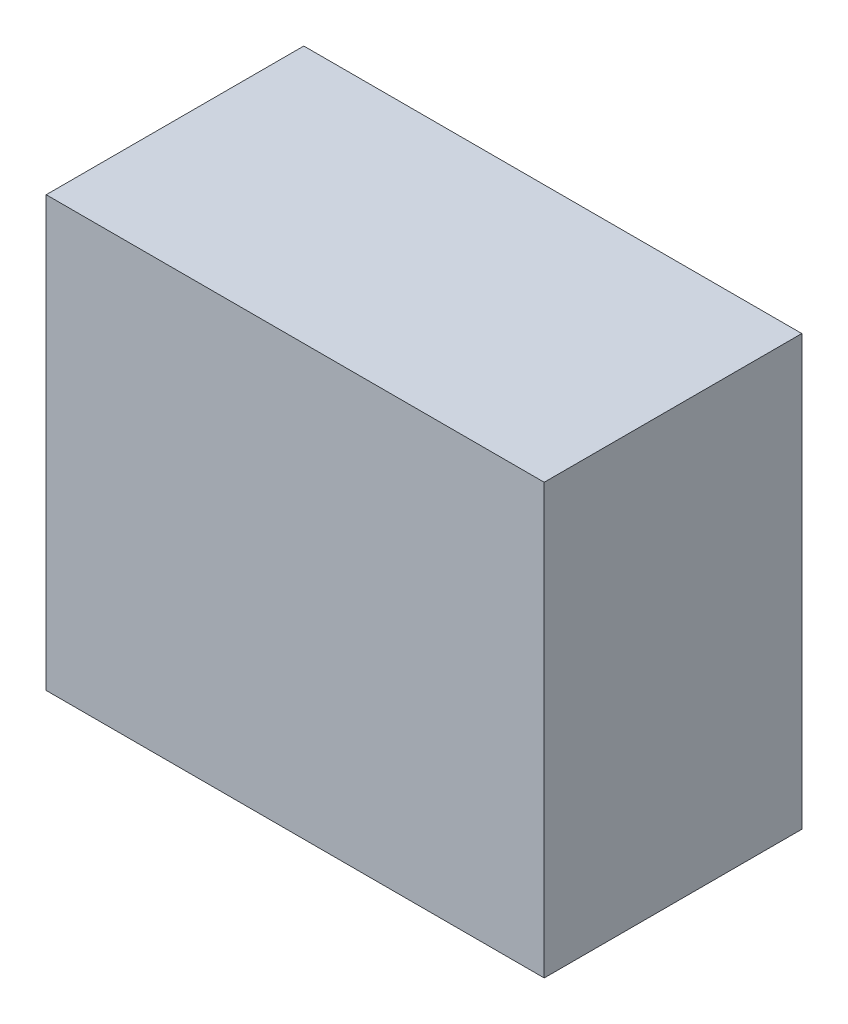
SolidWorks part; units mm, degrees
ref_plane "Front" through (0, 0, 0) normal (0, 0, 1) x (1, 0, 0)
ref_plane "Top" through (0, 0, 0) normal (0, 1, 0) x (1, 0, 0)
ref_plane "Right" through (0, 0, 0) normal (1, 0, 0) x (0, 0, -1)
sketch "Sketch1" plane through (0, 0, 0) normal (0, 0, 1) x (1, 0, 0)
  line L1 (0, 0) -> (29.464, 0)
  line L2 (0, 0) -> (0, 25.4)
  line L3 (0, 25.4) -> (29.464, 25.4)
  line L4 (29.464, 0) -> (29.464, 25.4)
  dimension "D1" = 29.464
  dimension "D2" = 25.4
extrude "Boss-Extrude1" add sketch "Sketch1" along normal blind 15.24
sketch "Sketch2" plane through (0, 0, 0) normal (0, -1, 0) x (1, 0, 0)
  line L0 (0, 0) -> (29.464, 0) construction
  line L1 (4.6228, 13.335) -> (24.765, 13.335)
  line L2 (4.6228, 13.335) -> (4.6228, 1.905)
  line L3 (4.6228, 1.905) -> (24.765, 1.905)
  line L4 (24.765, 13.335) -> (24.765, 1.905)
  line L6 (29.464, 15.24) -> (29.464, 0) construction
  dimension "D1" = 20.1422
  dimension "D2" = 11.43
  dimension "D3" = 1.905
  dimension "D4" = 4.699
extrude "Cut-Extrude1" cut sketch "Sketch2" against normal blind 22.86
